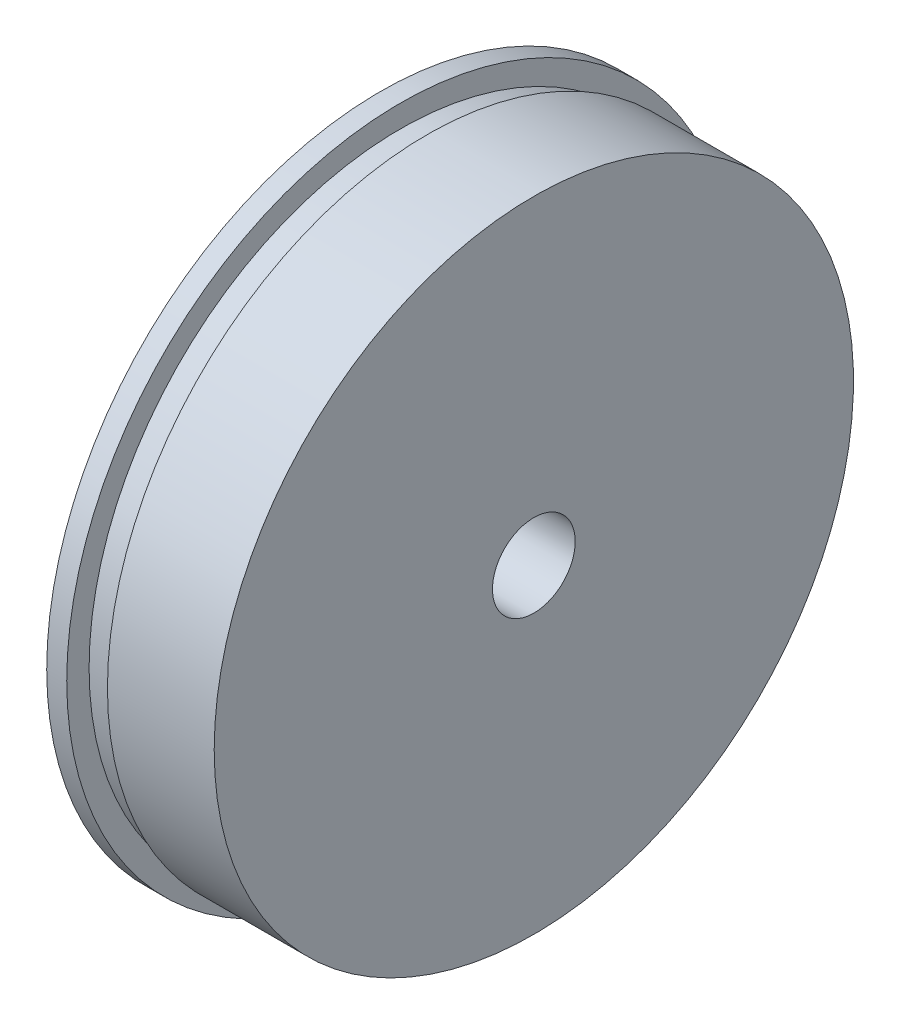
SolidWorks part; units mm, degrees
material "AISI 1020 Steel, Cold Rolled"
ref_plane "Front Plane" through (0, 0, 0) normal (0, 0, 1) x (1, 0, 0)
ref_plane "Top Plane" through (0, 0, 0) normal (0, 1, 0) x (1, 0, 0)
ref_plane "Right Plane" through (0, 0, 0) normal (1, 0, 0) x (0, 0, -1)
sketch "Sketch2" plane through (0, 0, 0) normal (0, 0, 1) x (1, 0, 0)
  line L0 (0, 0) -> (50000, 0) construction
  line L1 (0, 0) -> (0, -12.7)
  line L2 (0, -12.7) -> (0.762, -12.7)
  line L3 (0.762, -12.7) -> (0.762, -11.8491)
  line L4 (0.762, -11.8491) -> (1.778, -11.8491)
  line L5 (1.778, -11.8491) -> (1.778, -12.1666)
  line L6 (1.778, -12.1666) -> (5.842, -12.1666)
  line L7 (5.842, -12.1666) -> (5.842, 0)
  line L8 (0, 0) -> (5.842, 0)
  dimension "D1" = 24.3332
  dimension "D2" = 23.6982
  dimension "D3" = 25.4
  dimension "D4" = 0.762
  dimension "D5" = 1.016
  dimension "D6" = 5.842
revolve "Revolve1" add sketch "Sketch2" angle 360 about L0
sketch "Sketch3" plane through (5.842, 0, 0) normal (1, 0, 0) x (0, 0, -1)
  circle A0 centre (0, 0) radius 1.5748
  dimension "D1" = 3.1496
extrude "Cut-Extrude1" cut sketch "Sketch3" against normal through all
